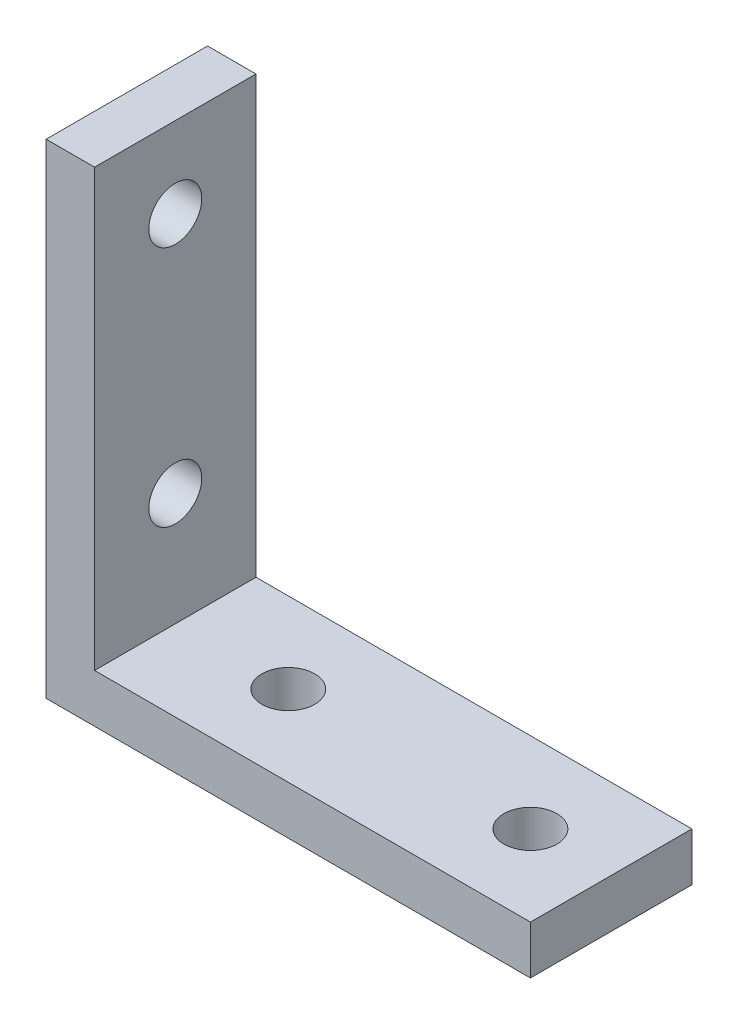
SolidWorks part; units mm, degrees
ref_plane "Front Plane" through (0, 0, 0) normal (0, 0, 1) x (1, 0, 0)
ref_plane "Top Plane" through (0, 0, 0) normal (0, 1, 0) x (1, 0, 0)
ref_plane "Right Plane" through (0, 0, 0) normal (1, 0, 0) x (0, 0, -1)
sketch "Sketch1" plane through (0, 0, 0) normal (0, 1, 0) x (1, 0, 0)
  line L1 (0, 0) -> (38.1, 0)
  line L2 (0, 0) -> (0, 12.7)
  line L3 (0, 12.7) -> (38.1, 12.7)
  line L4 (38.1, 0) -> (38.1, 12.7)
  circle A0 centre (12.7, 6.35) radius 2.0828
  circle A1 centre (31.75, 6.35) radius 2.0828
  point P9 (0, 0)
  dimension "D2" = 4.1656
  dimension "D3" = 4.1656
  dimension "D1" = 38.1
  dimension "D4" = 19.05
  dimension "D5" = 12.7
  dimension "D6" = 6.35
  dimension "D7" = 6.35
extrude "Boss-Extrude1" add sketch "Sketch1" along normal blind 3.81
sketch "Sketch2" plane through (0, 0, 0) normal (-1, 0, 0) x (0, 0, 1)
  line L1 (-12.7, 0) -> (0, 0)
  line L2 (-12.7, 0) -> (-12.7, 38.1)
  line L3 (-12.7, 38.1) -> (0, 38.1)
  line L4 (0, 0) -> (0, 38.1)
  circle A0 centre (-6.35, 31.75) radius 2.0828
  circle A1 centre (-6.35, 12.7) radius 2.0828
  dimension "D2" = 4.1656
  dimension "D3" = 4.1656
  dimension "D1" = 38.1
  dimension "D4" = 6.35
  dimension "D5" = 6.35
  dimension "D6" = 6.35
  dimension "D7" = 19.05
  dimension "D8" = 12.7
extrude "Boss-Extrude2" add sketch "Sketch2" against normal blind 3.81
